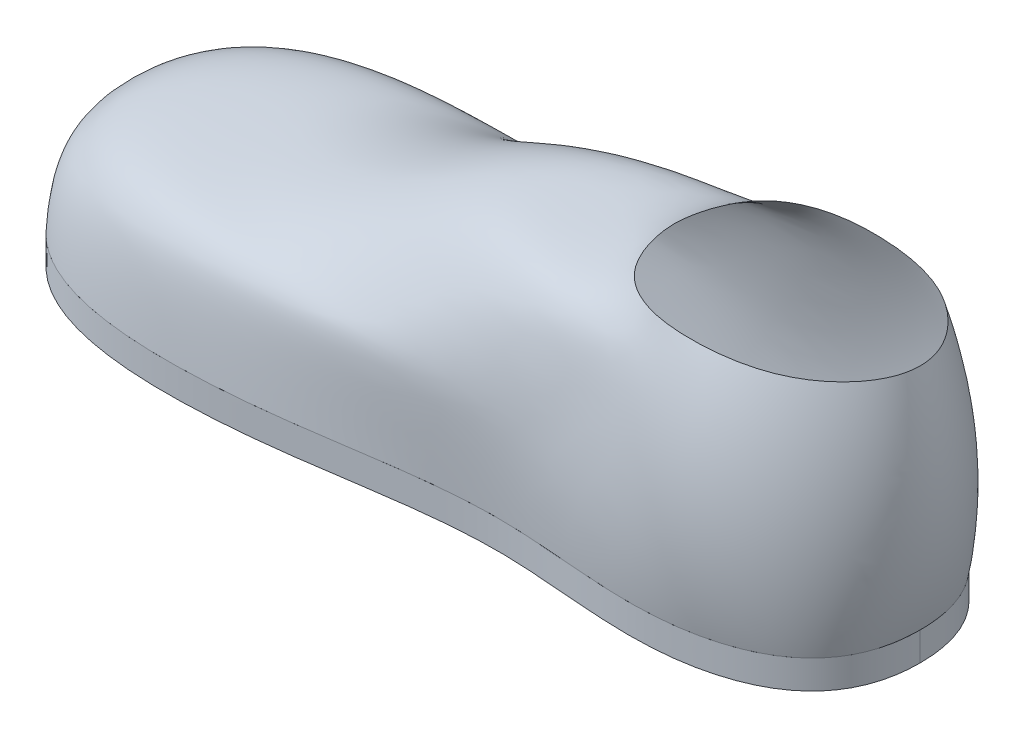
SolidWorks part; units mm, degrees
ref_plane "Front Plane" through (0, 0, 0) normal (0, 0, 1) x (1, 0, 0)
ref_plane "Top Plane" through (0, 0, 0) normal (0, 1, 0) x (1, 0, 0)
ref_plane "Right Plane" through (0, 0, 0) normal (1, 0, 0) x (0, 0, -1)
sketch "Sketch1" plane through (0, 0, 0) normal (0, 1, 0) x (1, 0, 0)
  line L0 (117.784, 0) -> (-117.784, 0) construction
  line L1 (0, 0) -> (0, 89.2828) construction
  line L2 (285, 0) -> (285, 64.9957) construction
  spline S0 degree 3 poles (0, 0) (0, 45.714) (90.8835, 57.2502) (167.9746, 33.01) (244.9596, 49.4693) (285, 25.3858) (285, 0) knots 0 0 0 0 0.296676 0.612721 0.832854 1 1 1 1
  spline S1 degree 3 poles (0, 0) (0, -45.714) (90.8835, -57.2502) (167.9746, -33.01) (244.9596, -49.4693) (285, -25.3858) (285, 0) knots 0 0 0 0 0.296676 0.612721 0.832854 1 1 1 1
  dimension "D1" = 50
  dimension "D2" = 40
  dimension "D3" = 40
  dimension "D4" = 35
  dimension "D5" = 285
  dimension "D6" = 80
  dimension "D7" = 105
extrude "Boss-Extrude1" add sketch "Sketch1" along normal blind 10
ref_plane "Plane1" through (0, 90, 0) normal (0, 1, 0) x (1, 0, 0)
sketch "Sketch3" plane through (0, 90, 0) normal (0, 1, 0) x (1, 0, 0)
  line L0 (0, 0) -> (292.2845, 0) construction
  line L1 (198.9078, 0) -> (198.9078, 24.3406) construction
  line L2 (198.9078, -26.4142) -> (198.9078, 26.4142) construction
  line L3 (285, 0) -> (285, 31.9036) construction
  spline S0 degree 3 poles (198.9078, 0) (198.9078, 6.1013) (205.1042, 29.2936) (241.3336, 34.5563) (272.779, 26.1247) (285, 8.1048) (285, 0) knots 0 0 0 0 0.183685 0.503014 0.802599 1 1 1 1
  spline S1 degree 3 poles (285, 0) (285, 25.3858) (244.9596, 49.4693) (167.9746, 33.01) (90.8835, 57.2502) (0, 45.714) (0, 0) knots 0 0 0 0 0.167146 0.387279 0.703324 1 1 1 1 construction
  spline S2 degree 3 poles (198.9078, 0) (198.9078, -6.1013) (205.1042, -29.2936) (241.3336, -34.5563) (272.779, -26.1247) (285, -8.1048) (285, 0) knots 0 0 0 0 0.183685 0.503014 0.802599 1 1 1 1
  point P6 (274.1995, 20.3867)
sketch3d "3DSketch1"
  spline S0 degree 2 poles (241.1344, 90, 31.9036) (243.2885, 50.9001, 48.121) (240.0608, 10, 41.759) knots 0 0 0 1 1 1
  spline S2 degree 3 poles (0, 10, 0) (0, 10, 45.714) (90.8835, 10, 57.2502) (167.9746, 10, 33.01) (244.9596, 10, 49.4693) (285, 10, 25.3858) (285, 10, 0) knots 0 0 0 0 0.296676 0.612721 0.832854 1 1 1 1 construction
  spline S3 degree 3 poles (198.9078, 90, 0) (198.9078, 90, 6.1013) (205.1042, 90, 29.2936) (241.3336, 90, 34.5563) (272.779, 90, 26.1247) (285, 90, 8.1048) (285, 90, 0) knots 0 0 0 0 0.183685 0.503014 0.802599 1 1 1 1 construction
  spline S4 degree 2 poles (241.1344, 90, -31.9036) (243.2885, 50.9001, -48.121) (240.0608, 10, -41.759) knots 0 0 0 1 1 1
  spline S5 degree 3 poles (198.9078, 90, 0) (198.9078, 90, -6.1013) (205.1042, 90, -29.2936) (241.3336, 90, -34.5563) (272.779, 90, -26.1247) (285, 90, -8.1048) (285, 90, 0) knots 0 0 0 0 0.183685 0.503014 0.802599 1 1 1 1 construction
  spline S6 degree 3 poles (285, 10, 0) (285, 10, -25.3858) (244.9596, 10, -49.4693) (167.9746, 10, -33.01) (90.8835, 10, -57.2502) (0, 10, -45.714) (0, 10, 0) knots 0 0 0 0 0.167146 0.387279 0.703324 1 1 1 1 construction
  spline S7 degree 2 poles (285, 90, 0) (298.0305, 50.0035, 0) (285, 10, 0) knots 0 0 0 1 1 1
  point P2 (0, 0, 0)
  point P4 (241.7021, 39.6832, -43.392)
  point P5 (0, 0, 0)
  point P11 (0, 0, 0)
  point P12 (0, 0, 0)
sketch "Sketch4" plane through (0, 0, 0) normal (0, 0, 1) x (1, 0, 0)
  line L0 (0, 90) -> (292.2845, 90) construction
  line L1 (285, 90) -> (198.9078, 90) construction
  line L2 (0, 10) -> (0, 61.1884) construction
  spline S0 degree 3 poles (0, 10) (0, 29.9307) (15.3885, 52.2631) (67.8734, 47.5595) (110.8089, 64.2898) (152.7198, 87.2831) (184.4951, 80.8222) (198.9078, 90) knots 0 0 0 0 0.169151 0.389348 0.603579 0.788324 1 1 1 1
  point P4 (0, 10)
  point P6 (0, 0)
sketch "Sketch5" plane through (0, 10, 0) normal (0, 1, 0) x (1, 0, 0)
  spline S2 degree 3 poles (2173.9438, 2055.1906) (-309.0355, 39.4748) (14.0331, -81.4147) (167.9746, -33.01) (324.0149, -66.3714) (426.167, 179.7209) (-2041.8226, 1880.1461) knots -0.830252 -0.830252 -0.830252 -0.830252 0.296676 0.612721 0.832854 1.722238 1.722238 1.722238 1.722238 only from (0, 0) to (285, 0)
  spline S3 degree 3 poles (-2041.8081, -1880.1361) (426.1667, -179.7201) (324.0147, 66.3713) (167.9746, 33.01) (14.0322, 81.415) (-309.04, -39.4765) (2174.0107, -2055.2449) knots -0.722236 -0.722236 -0.722236 -0.722236 0.167146 0.387279 0.703324 1.830262 1.830262 1.830262 1.830262 only from (285, 0) to (0, 0)
  spline S4 degree 3 poles (0, 0) (0, -45.714) (90.8835, -57.2502) (167.9746, -33.01) (244.9596, -49.4693) (285, -25.3858) (285, 0) knots 0 0 0 0 0.296676 0.612721 0.832854 1 1 1 1
  spline S5 degree 3 poles (285, 0) (285, 25.3858) (244.9596, 49.4693) (167.9746, 33.01) (90.8835, 57.2502) (0, 45.714) (0, 0) knots 0 0 0 0 0.167146 0.387279 0.703324 1 1 1 1
  dimension "D1" = 0
surface "Surface-Loft1"
